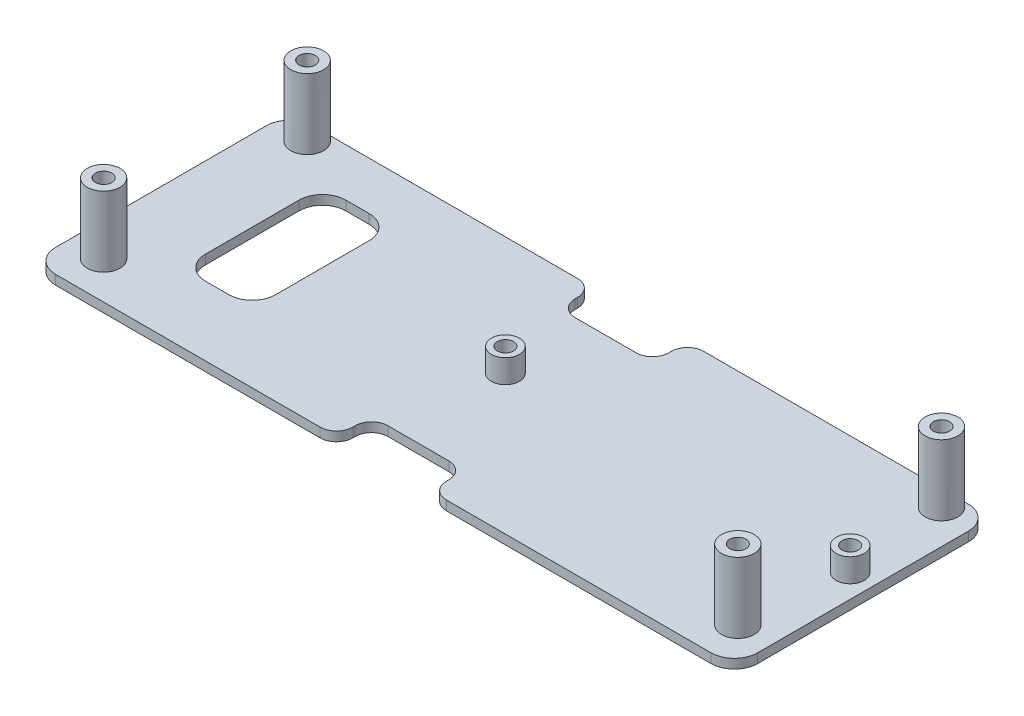
SolidWorks part; units mm, degrees
ref_plane "Front Plane" through (0, 0, 0) normal (0, 0, 1) x (1, 0, 0)
ref_plane "Top Plane" through (0, 0, 0) normal (0, 1, 0) x (1, 0, 0)
ref_plane "Right Plane" through (0, 0, 0) normal (1, 0, 0) x (0, 0, -1)
sketch "Sketch1" plane through (0, 0, 0) normal (0, 1, 0) x (1, 0, 0)
  line L1 (-75, -27.5) -> (75, -27.5)
  line L2 (-75, -27.5) -> (-75, 27.5)
  line L3 (-75, 27.5) -> (75, 27.5)
  line L4 (75, -27.5) -> (75, 27.5)
  line L5 (-75, -27.5) -> (75, 27.5) construction
  line L6 (-75, 27.5) -> (75, -27.5) construction
  line L7 (-67.75, -19.5) -> (67.75, -19.5) construction
  line L8 (-67.75, -19.5) -> (-67.75, 24) construction
  line L9 (-67.75, 24) -> (67.75, 24) construction
  line L10 (67.75, -19.5) -> (67.75, 24) construction
  line L11 (-57.75, 17.25) -> (-42.75, 17.25)
  line L12 (-57.75, 17.25) -> (-57.75, -12.75)
  line L13 (-57.75, -12.75) -> (-42.75, -12.75)
  line L14 (-42.75, 17.25) -> (-42.75, -12.75)
  line L15 (-10, 27.5) -> (10, 27.5)
  line L16 (-10, 27.5) -> (-10, 20)
  line L17 (-10, 20) -> (10, 20)
  line L18 (10, 27.5) -> (10, 20)
  line L19 (-10, -27.5) -> (10, -27.5)
  line L20 (-10, -27.5) -> (-10, -20)
  line L21 (-10, -20) -> (10, -20)
  line L22 (10, -27.5) -> (10, -20)
  point P0 (0, 0)
  point P10 (0, 24)
  point P15 (-67.75, 2.25)
  point P16 (-57.75, 2.25)
  point P21 (0, 20)
  dimension "D1" = 55
  dimension "D2" = 150
  dimension "D3" = 135.5
  dimension "D4" = 43.5
  dimension "D5" = 3.5
  dimension "D6" = 15
  dimension "D7" = 30
  dimension "D8" = 10
  dimension "D9" = 7.5
  dimension "D10" = 20
extrude "Boss-Extrude1" add sketch "Sketch1" along normal blind 2 contours L3 L18 L17 L16 L2 L1 L4 L11 L14 L13 L12
sketch "Sketch2" plane through (0, 2, 0) normal (0, 1, 0) x (1, 0, 0)
  line L0 (-67.75, -19.5) -> (-67.75, 24) construction
  line L1 (-67.75, -19.5) -> (67.75, -19.5) construction
  line L2 (67.75, -19.5) -> (67.75, 24) construction
  line L3 (-67.75, 24) -> (67.75, 24) construction
  line L4 (-67.75, -19.5) -> (-67.75, 24) construction
  line L5 (-67.75, -19.5) -> (67.75, -19.5) construction
  line L6 (67.75, -19.5) -> (67.75, 24) construction
  line L7 (-67.75, 24) -> (67.75, 24) construction
  line L9 (-75, 27.5) -> (-10, 27.5) construction
  circle A0 centre (-67.75, -19.5) radius 3.5
  circle A1 centre (-67.75, 24) radius 3.5
  circle A2 centre (67.75, 24) radius 3.5
  circle A3 centre (67.75, -19.5) radius 3.5
extrude "Boss-Extrude2" add sketch "Sketch2" along normal blind 15
sketch "Sketch3" plane through (0, 17, 0) normal (0, 1, 0) x (1, 0, 0)
  circle A0 centre (-67.75, -19.5) radius 1.75
  circle A1 centre (-67.75, 24) radius 1.75
  circle A2 centre (67.75, 24) radius 1.75
  circle A3 centre (67.75, -19.5) radius 1.75
  dimension "D1" = 3.5
extrude "Cut-Extrude1" cut sketch "Sketch3" against normal up to next
sketch "Sketch4" plane through (0, 2, 0) normal (0, 1, 0) x (1, 0, 0)
  line L1 (67.75, -19.5) -> (67.75, 24) construction
  line L2 (75, -27.5) -> (75, 27.5) construction
  circle A0 centre (-3.66, 2.25) radius 3
  circle A1 centre (70, 2.25) radius 3
  circle A2 centre (70, 2.25) radius 1.75
  circle A3 centre (-3.66, 2.25) radius 1.75
  point P8 (67.75, 2.25)
  dimension "D1" = 6
  dimension "D4" = 3.5
  dimension "D2" = 73.66
  dimension "D3" = 5
extrude "Boss-Extrude3" add sketch "Sketch4" along normal blind 5
fillet "Fillet1" radius 5 8 edges at (75, 1, 27.5) (75, 1, -27.5) (-75, 1, -27.5) (-75, 1, 27.5) (-42.75, 1, 12.75) (-57.75, 1, 12.75) (-42.75, 1, -17.25) (-57.75, 1, -17.25)
fillet "Fillet2" radius 3.5 8 edges at (-10, 1, -27.5) (-10, 1, -20) (10, 1, -20) (10, 1, -27.5) (10, 1, 27.5) (10, 1, 20) (-10, 1, 20) (-10, 1, 27.5)
